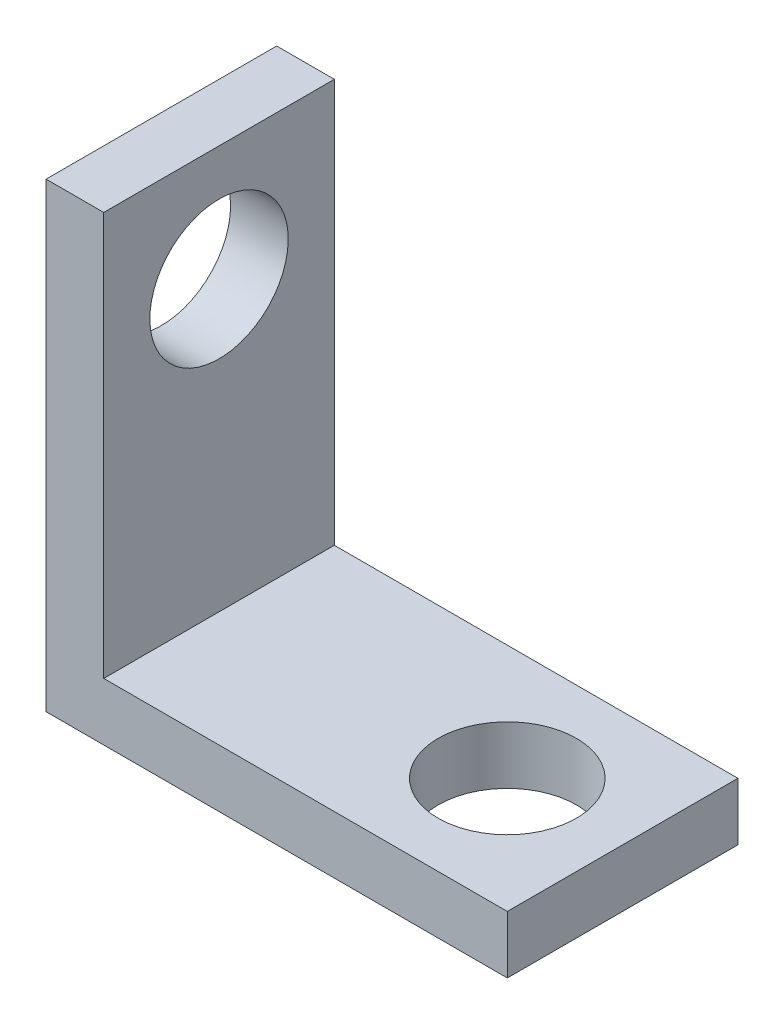
SolidWorks part; units mm, degrees
ref_plane "Front Plane" through (0, 0, 0) normal (0, 0, 1) x (1, 0, 0)
ref_plane "Top Plane" through (0, 0, 0) normal (0, 1, 0) x (1, 0, 0)
ref_plane "Right Plane" through (0, 0, 0) normal (1, 0, 0) x (0, 0, -1)
sketch "Sketch1" plane through (0, 0, 0) normal (0, 0, 1) x (1, 0, 0)
  line L0 (0, 0) -> (0, 25.4)
  line L1 (0, 25.4) -> (3.175, 25.4)
  line L2 (3.175, 25.4) -> (3.175, 3.175)
  line L3 (3.175, 3.175) -> (25.4, 3.175)
  line L4 (25.4, 3.175) -> (25.4, 0)
  line L5 (25.4, 0) -> (0, 0)
  dimension "D1" = 3.175
  dimension "D2" = 3.175
  dimension "D3" = 25.4
  dimension "D4" = 25.4
extrude "Boss-Extrude1" add sketch "Sketch1" along normal blind 12.7
sketch "Sketch2" plane through (0, 3.175, 0) normal (0, 1, 0) x (1, 0, 0)
  line L0 (25.4, 0) -> (3.175, 0) construction
  line L1 (25.4, -12.7) -> (25.4, 0) construction
  circle A0 centre (19.05, -6.35) radius 3.81
  dimension "D1" = 6.35
  dimension "D2" = 6.35
extrude "Cut-Extrude1" cut sketch "Sketch2" against normal blind 12.7
sketch "Sketch3" plane through (3.175, 0, 0) normal (1, 0, 0) x (0, 0, -1)
  line L0 (-12.7, 3.175) -> (-12.7, 25.4) construction
  line L1 (-12.7, 25.4) -> (0, 25.4) construction
  circle A0 centre (-6.35, 19.05) radius 3.81
  dimension "D1" = 6.35
  dimension "D2" = 6.35
extrude "Cut-Extrude2" cut sketch "Sketch3" against normal blind 12.7
